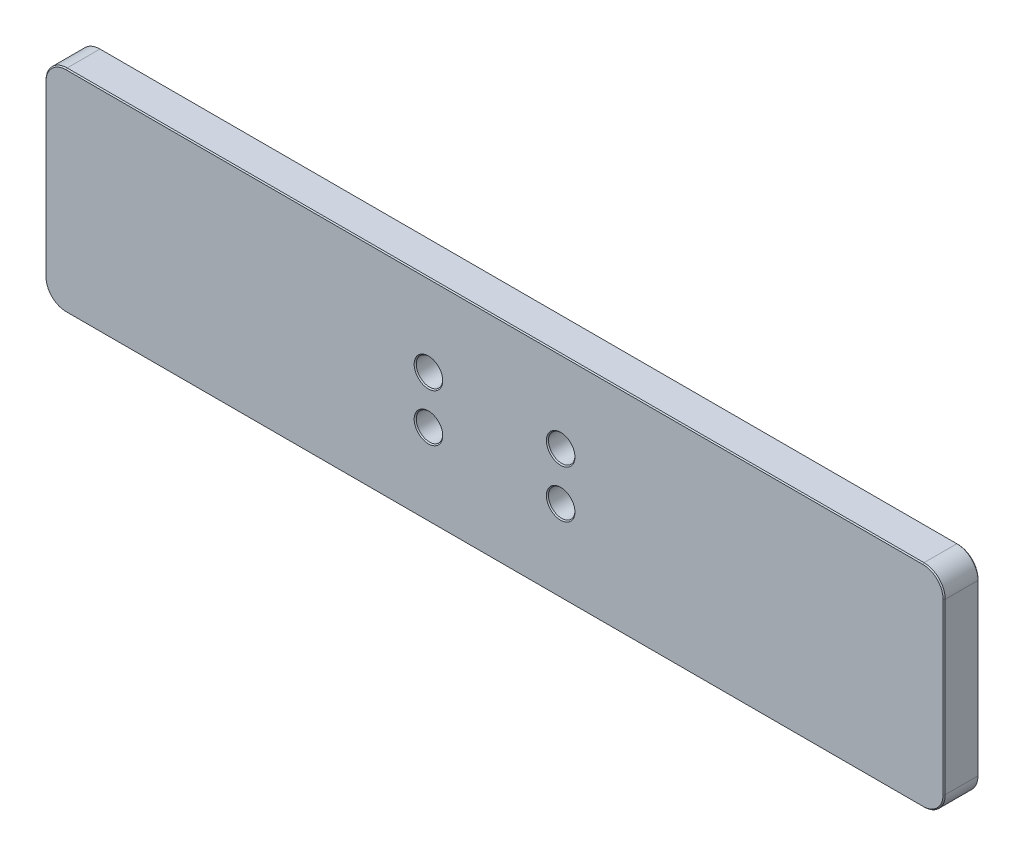
SolidWorks part; units mm, degrees
ref_plane "Front Plane" through (0, 0, 0) normal (0, 0, 1) x (1, 0, 0)
ref_plane "Top Plane" through (0, 0, 0) normal (0, 1, 0) x (1, 0, 0)
ref_plane "Right Plane" through (0, 0, 0) normal (1, 0, 0) x (0, 0, -1)
sketch "Sketch1" plane through (0, 0, 0) normal (0, 0, 1) x (1, 0, 0)
  line L0 (-15.875, 5.715) -> (-15.875, -5.715) construction
  line L1 (107.95, -25.4) -> (-107.95, -25.4)
  line L2 (107.95, -25.4) -> (107.95, 25.4)
  line L3 (107.95, 25.4) -> (-107.95, 25.4)
  line L4 (-107.95, -25.4) -> (-107.95, 25.4)
  line L5 (107.95, -25.4) -> (-107.95, 25.4) construction
  line L6 (107.95, 25.4) -> (-107.95, -25.4) construction
  line L7 (-15.875, -5.715) -> (15.875, -5.715) construction
  line L8 (15.875, -5.715) -> (15.875, 5.715) construction
  line L9 (15.875, 5.715) -> (-15.875, 5.715) construction
  line L10 (15.875, -5.715) -> (-15.875, 5.715) construction
  line L11 (-15.875, -5.715) -> (15.875, 5.715) construction
  line L12 (-15.875, 5.715) -> (15.875, -5.715) construction
  line L13 (15.875, 5.715) -> (-15.875, -5.715) construction
  circle A0 centre (-15.875, 5.715) radius 3.175
  circle A1 centre (15.875, 5.715) radius 3.175
  circle A2 centre (15.875, -5.715) radius 3.175
  circle A3 centre (-15.875, -5.715) radius 3.175
  point P0 (0, 0)
  point P6 (0, 0)
  point P7 (0, 0)
  point P9 (0, 0)
  point P10 (0, 0)
  point P18 (0, 0)
  point P19 (0, 0)
  point P20 (0, 0)
  dimension "D4" = 6.35
  dimension "D1" = 215.9
  dimension "D2" = 50.8
  dimension "D3" = 31.75
  dimension "D5" = 11.43
extrude "Boss-Extrude1" add sketch "Sketch1" along normal blind 8.382
fillet "Fillet1" radius 5.08 4 edges at (-107.95, -25.4, 4.191) (107.95, -25.4, 4.191) (107.95, 25.4, 4.191) (-107.95, 25.4, 4.191)
chamfer "Chamfer1" distance 0.254 angle 45 24 edges at (-12.7, -5.715, 0) (19.05, -5.715, 0) (19.05, 5.715, 0) (-12.7, 5.715, 0) (106.4621, -23.9121, 0) (107.95, 0, 0) (106.4621, 23.9121, 0) (0, 25.4, 0) (-106.4621, 23.9121, 0) (-107.95, 0, 0) (-106.4621, -23.9121, 0) (0, -25.4, 0) (-12.7, -5.715, 8.382) (19.05, 5.715, 8.382) (-106.4621, 23.9121, 8.382) (0, 25.4, 8.382) (106.4621, 23.9121, 8.382) (107.95, 0, 8.382) (106.4621, -23.9121, 8.382) (0, -25.4, 8.382) (-106.4621, -23.9121, 8.382) (-107.95, 0, 8.382) (-12.7, 5.715, 8.382) (19.05, -5.715, 8.382)
